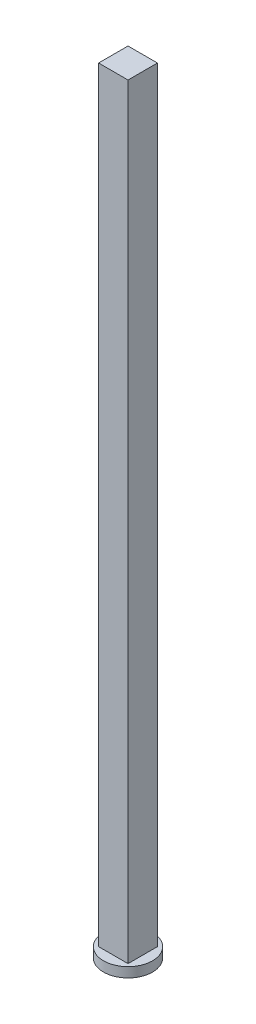
SolidWorks part; units mm, degrees
ref_plane "Plan de face" through (0, 0, 0) normal (0, 0, 1) x (1, 0, 0)
ref_plane "Plan de dessus" through (0, 0, 0) normal (0, 1, 0) x (1, 0, 0)
ref_plane "Plan de droite" through (0, 0, 0) normal (1, 0, 0) x (0, 0, -1)
sketch "Esquisse1" plane through (0, 0, 0) normal (0, 1, 0) x (1, 0, 0)
  line L1 (-1.5, -1.5) -> (1.5, -1.5)
  line L2 (-1.5, -1.5) -> (-1.5, 1.5)
  line L3 (-1.5, 1.5) -> (1.5, 1.5)
  line L4 (1.5, -1.5) -> (1.5, 1.5)
  line L5 (-1.5, -1.5) -> (1.5, 1.5) construction
  line L6 (-1.5, 1.5) -> (1.5, -1.5) construction
  point P0 (0, 0)
  dimension "D1" = 3
  dimension "D2" = 3
extrude "Boss.-Extru.1" add sketch "Esquisse1" along normal blind 95
sketch "Esquisse2" plane through (0, 0, 0) normal (0, -1, 0) x (1, 0, 0)
  circle A0 centre (0, 0) radius 2.5
  dimension "D1" = 5
extrude "Boss.-Extru.2" add sketch "Esquisse2" along normal blind 1
sketch "Esquisse3" plane through (0, 95, 0) normal (0, 1, 0) x (1, 0, 0)
  line L1 (-1.5, -1.5) -> (1.5, -1.5)
  line L2 (-1.5, -1.5) -> (-1.5, 1.5)
  line L3 (-1.5, 1.5) -> (1.5, 1.5)
  line L4 (1.5, -1.5) -> (1.5, 1.5)
  line L5 (-1.5, -1.5) -> (1.5, 1.5) construction
  line L6 (-1.5, 1.5) -> (1.5, -1.5) construction
  point P0 (0, 0)
extrude "Enlèv. mat.-Extru.1" cut sketch "Esquisse3" against normal blind 17
equation "\"D2@Esquisse1\"=\"D1@Esquisse1\""
